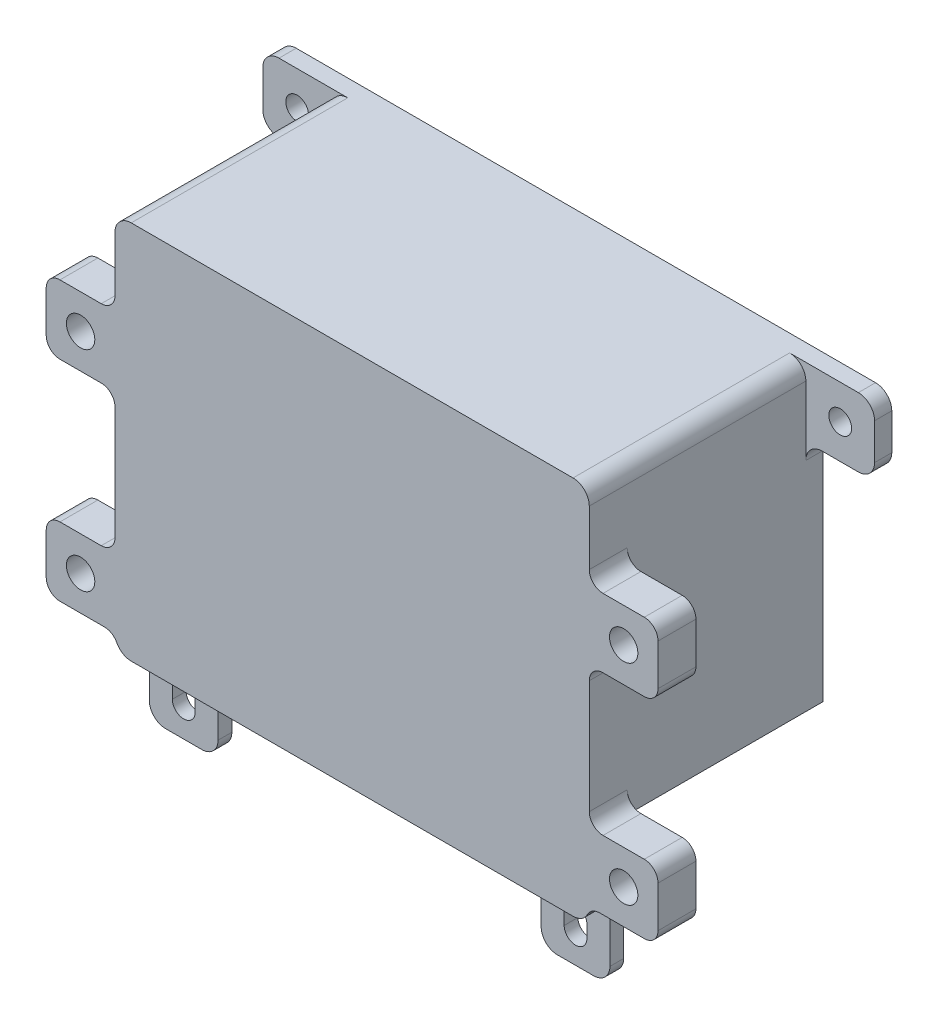
SolidWorks part; units mm, degrees
material "ABS"
ref_plane "X-Y Datum" through (0, 0, 0) normal (0, 0, 1) x (1, 0, 0)
ref_plane "X-Z Datum" through (0, 0, 0) normal (0, 1, 0) x (1, 0, 0)
ref_plane "Y-Z Datum" through (0, 0, 0) normal (1, 0, 0) x (0, 0, -1)
sketch "Sketch1" plane through (0, 0, 0) normal (0, 0, 1) x (1, 0, 0)
  line L0 (6.33, 73.27) -> (88.87, 73.27)
  line L1 (7.6, 72) -> (87.6, 72) construction
  line L2 (7.6, 72) -> (7.6, 9.5) construction
  line L3 (7.6, 9.5) -> (87.6, 9.5) construction
  line L4 (87.6, 72) -> (87.6, 9.5) construction
  line L5 (88.87, 73.27) -> (88.87, 8.23)
  line L6 (6.33, 8.23) -> (88.87, 8.23)
  line L7 (6.33, 73.27) -> (6.33, 8.23)
  circle A0 centre (12.6, 67) radius 2.125 construction
  circle A1 centre (82.6, 67) radius 2.125 construction
  circle A2 centre (82.6, 17) radius 2.125 construction
  circle A3 centre (12.6, 17) radius 2.125 construction
  dimension "D1" = 1.27
extrude "Boss-Extrude1" add sketch "Sketch1" along normal blind 43.18
shell "Shell1" thickness 2.54
sketch "Sketch6" plane through (3.79, 0, 0) normal (-1, 0, 0) x (0, 0, 1)
  line L24 (0, 81.9051) -> (38.1, 81.9051) construction
  line L25 (2.54, 59.03) -> (2.54, 73.27)
  line L26 (0, 59.03) -> (0, 3.15)
  line L27 (38.1, 3.15) -> (0, 3.15)
  line L28 (38.1, 19.9292) -> (38.1, 3.15)
  line L30 (2.54, 73.27) -> (0, 73.27)
  line L31 (0, 73.27) -> (0, 59.03)
  line L32 (20.32, 59.03) -> (20.32, 19.9292) construction
  line L34 (2.54, 19.9292) -> (38.1, 19.9292)
  line L35 (2.54, 59.03) -> (2.54, 19.9292)
  point P0 (0, 73.27)
extrude "Cut-Extrude2" cut sketch "Sketch6" against normal through all
sketch "Sketch7" plane through (0, 73.27, 0) normal (0, 1, 0) x (1, 0, 0)
  line L1 (3.79, -45.72) -> (91.41, -45.72)
  line L2 (3.79, -45.72) -> (3.79, -2.54)
  line L3 (3.79, -2.54) -> (91.41, -2.54)
  line L4 (91.41, -45.72) -> (91.41, -2.54)
extrude "Boss-Extrude2" add sketch "Sketch7" along normal blind 2.54
sketch "Sketch8" plane through (0, 0, 2.54) normal (0, 0, -1) x (-1, 0, 0)
  line L0 (-65.4056, 75.81) -> (-65.4056, 73.27)
  line L3 (-88.87, 73.27) -> (-6.33, 73.27) construction
  line L4 (-90.14, 19.9292) -> (-90.14, 74.54)
  line L5 (-91.41, 19.9292) -> (-88.87, 19.9292) construction
  line L6 (-5.06, 19.9292) -> (-5.06, 74.54)
  line L7 (-6.33, 19.9292) -> (-3.79, 19.9292) construction
  line L8 (-5.06, 74.54) -> (-90.14, 74.54)
  line L9 (-90.14, 19.9292) -> (-88.87, 19.9292)
  line L10 (-88.87, 19.9292) -> (-88.87, 73.27)
  line L11 (-88.87, 73.27) -> (-6.33, 73.27)
  line L12 (-6.33, 73.27) -> (-6.33, 19.9292)
  line L13 (-6.33, 19.9292) -> (-3.79, 19.9292) construction
  line L14 (-6.33, 19.9292) -> (-5.06, 19.9292)
  line M2 (-6.33, 73.27) -> (-6.33, 19.9292)
  line M3 (-6.33, 19.9292) -> (-3.79, 19.9292)
  line M7 (-91.41, 19.9292) -> (-88.87, 19.9292)
  line M8 (-88.87, 19.9292) -> (-88.87, 73.27)
  line M9 (-88.87, 73.27) -> (-6.33, 73.27)
extrude "Cut-Extrude3" cut sketch "Sketch8" against normal blind 2.54 contours L0 L8 L4 M7 M8 M9 | L6 L8 L0 M9 M2 M3
sketch "Sketch9" plane through (0, 0, 38.1) normal (0, 0, -1) x (-1, 0, 0)
  line L3 (-90.14, 19.9292) -> (-90.14, 6.96)
  line L4 (-90.14, 6.96) -> (-5.06, 6.96)
  line L5 (-5.06, 6.96) -> (-5.06, 19.9292)
  line L6 (-6.33, 19.9292) -> (-3.79, 19.9292) construction
  line L7 (-5.06, 19.9292) -> (-6.33, 19.9292)
  line L8 (-6.33, 19.9292) -> (-6.33, 8.23)
  line L9 (-6.33, 8.23) -> (-88.87, 8.23)
  line L10 (-88.87, 8.23) -> (-88.87, 19.9292)
  line L11 (-88.87, 19.9292) -> (-90.14, 19.9292)
extrude "Cut-Extrude4" cut sketch "Sketch9" against normal blind 2.54
sketch "Sketch10" plane through (0, 19.9292, 0) normal (0, -1, 0) x (1, 0, 0)
  line L1 (5.06, 5.08) -> (6.33, 5.08)
  line L2 (5.06, 5.08) -> (5.06, 40.64)
  line L3 (5.06, 40.64) -> (6.33, 40.64)
  line L4 (6.33, 5.08) -> (6.33, 40.64)
  line L5 (90.14, 5.08) -> (88.87, 5.08)
  line L6 (90.14, 5.08) -> (90.14, 40.64)
  line L7 (90.14, 40.64) -> (88.87, 40.64)
  line L8 (88.87, 5.08) -> (88.87, 40.64)
extrude "Cut-Extrude5" cut sketch "Sketch10" against normal blind 2.54
sketch "Sketch11" plane through (0, 5.69, 0) normal (0, -1, 0) x (1, 0, 0)
  line L0 (90.14, 5.08) -> (90.14, 40.64) construction
  line L1 (5.06, 38.1) -> (17.76, 38.1)
  line L2 (5.06, 38.1) -> (5.06, 40.64)
  line L3 (5.06, 40.64) -> (17.76, 40.64)
  line L4 (17.76, 38.1) -> (17.76, 40.64)
  line L5 (90.14, 38.1) -> (77.44, 38.1)
  line L6 (90.14, 38.1) -> (90.14, 40.64)
  line L7 (90.14, 40.64) -> (77.44, 40.64)
  line L8 (77.44, 38.1) -> (77.44, 40.64)
  line L9 (91.41, 38.1) -> (90.14, 38.1) construction
extrude "Boss-Extrude3" add sketch "Sketch11" along normal blind 12.7
sketch "Sketch12" plane through (0, 0, 40.64) normal (0, 0, 1) x (1, 0, 0)
  line L0 (11.41, -0.6201) -> (11.41, 0.61) construction
  line L3 (11.41, -0.6201) -> (11.41, -1.6835) construction
  line L4 (9.31, 0.61) -> (9.31, -1.6835)
  line L5 (13.51, 0.61) -> (13.51, -1.6835)
  line L6 (47.6, 5.69) -> (47.6, 25.4131) construction
  line L7 (3.79, 5.69) -> (91.41, 5.69) construction
  line L8 (83.79, -0.6201) -> (83.79, -1.6835) construction
  line L9 (83.79, -0.6201) -> (83.79, 0.61) construction
  line L10 (81.69, 0.61) -> (81.69, -1.6835)
  line L11 (85.89, 0.61) -> (85.89, -1.6835)
  arc A0 (13.51, 0.61) -> (9.31, 0.61) centre (11.41, 0.61) ccw
  arc A1 (9.31, -1.6835) -> (13.51, -1.6835) centre (11.41, -1.6835) ccw
  arc A2 (85.89, -1.6835) -> (81.69, -1.6835) centre (83.79, -1.6835) cw
  arc A3 (81.69, 0.61) -> (85.89, 0.61) centre (83.79, 0.61) cw
  point P6 (11.41, -0.6201)
  point P19 (83.79, -0.6201)
ref_plane "Plane1" through (47.6, 0, 0) normal (-1, 0, 0) x (0, 0, 1)
extrude "Cut-Extrude7" cut sketch "Sketch12" against normal through all
sketch "Sketch13" plane through (0, 0, 2.54) normal (0, 0, -1) x (-1, 0, 0)
  line L1 (-91.41, 75.81) -> (-104.11, 75.81)
  line L2 (-91.41, 75.81) -> (-91.41, 63.11)
  line L3 (-91.41, 63.11) -> (-104.11, 63.11)
  line L4 (-104.11, 75.81) -> (-104.11, 63.11)
  line L5 (-3.79, 75.81) -> (8.91, 75.81)
  line L6 (-3.79, 75.81) -> (-3.79, 63.11)
  line L7 (-3.79, 63.11) -> (8.91, 63.11)
  line L8 (8.91, 75.81) -> (8.91, 63.11)
  circle A0 centre (-97.76, 69.46) radius 2.1
  circle A1 centre (2.56, 69.46) radius 2.1
extrude "Boss-Extrude4" add sketch "Sketch13" against normal blind 3.175
fillet "Fillet2" radius 3 16 edges at (77.44, 5.69, 39.37) (77.44, -7.01, 39.37) (90.14, -7.01, 39.37) (17.76, -7.01, 39.37) (5.06, -7.01, 39.37) (17.76, 5.69, 39.37) (3.79, 63.11, 4.1275) (-8.91, 63.11, 4.1275) (-8.91, 75.81, 4.1275) (91.41, 63.11, 4.1275) (104.11, 63.11, 4.1275) (104.11, 75.81, 4.1275) (91.41, 75.81, 25.7175) (3.79, 75.81, 25.7175) (3.79, 5.69, 41.91) (91.41, 5.69, 41.91)
sketch "Sketch14" plane through (0, 0, 45.72) normal (0, 0, 1) x (1, 0, 0)
  line L5 (47.6, 23.749) -> (47.6, -23.749) construction
  line L11 (3.79, 60.11) -> (-8.91, 60.11)
  line L12 (3.79, 60.11) -> (3.79, 47.41)
  line L13 (3.79, 47.41) -> (-8.91, 47.41)
  line L14 (-8.91, 60.11) -> (-8.91, 47.41)
  line L15 (3.79, 8.69) -> (-8.91, 8.69)
  line L16 (3.79, 8.69) -> (3.79, 21.39)
  line L17 (3.79, 21.39) -> (-8.91, 21.39)
  line L18 (-8.91, 8.69) -> (-8.91, 21.39)
  line L19 (91.41, 21.39) -> (104.11, 21.39)
  line L20 (104.11, 8.69) -> (104.11, 21.39)
  line L21 (91.41, 8.69) -> (104.11, 8.69)
  line L22 (91.41, 8.69) -> (91.41, 21.39)
  line L23 (91.41, 47.41) -> (104.11, 47.41)
  line L24 (104.11, 60.11) -> (104.11, 47.41)
  line L25 (91.41, 60.11) -> (104.11, 60.11)
  line L26 (91.41, 60.11) -> (91.41, 47.41)
  circle A5 centre (-2.56, 53.76) radius 2.625
  circle A6 centre (-2.56, 15.04) radius 2.625
  circle A7 centre (97.76, 15.04) radius 2.625
  circle A8 centre (97.76, 53.76) radius 2.625
extrude "Boss-Extrude5" add sketch "Sketch14" against normal blind 7
fillet "Fillet3" radius 2.54 16 edges at (3.79, 60.11, 42.22) (-8.91, 60.11, 42.22) (-8.91, 47.41, 42.22) (3.79, 47.41, 42.22) (3.79, 21.39, 42.22) (-8.91, 21.39, 42.22) (-8.91, 8.69, 42.22) (3.79, 8.69, 42.22) (91.41, 8.69, 42.22) (104.11, 8.69, 42.22) (104.11, 21.39, 42.22) (91.41, 21.39, 42.22) (91.41, 60.11, 42.22) (104.11, 60.11, 42.22) (104.11, 47.41, 42.22) (91.41, 47.41, 42.22)
sketch "Sketch15" plane through (0, 0, 45.72) normal (0, 0, 1) x (1, 0, 0)
  line L1 (-8.91, 8.69) -> (6.79, 8.69)
  line L2 (-8.91, 8.69) -> (-8.91, 75.81)
  line L3 (-8.91, 75.81) -> (6.79, 75.81)
  line L4 (6.79, 8.69) -> (6.79, 60.8535)
  line L5 (104.11, 8.69) -> (88.41, 8.69)
  line L6 (104.11, 8.69) -> (104.11, 75.81)
  line L7 (104.11, 75.81) -> (88.41, 75.81)
  line L8 (88.41, 8.69) -> (88.41, 60.8535)
  line L9 (6.79, 75.81) -> (88.41, 75.81)
  line L11 (6.79, 60.8535) -> (88.41, 60.8535)
  circle A0 centre (-2.56, 53.76) radius 2.625
  circle A1 centre (-2.56, 15.04) radius 2.625
  circle A2 centre (97.76, 15.04) radius 2.625
  circle A3 centre (97.76, 53.76) radius 2.625
